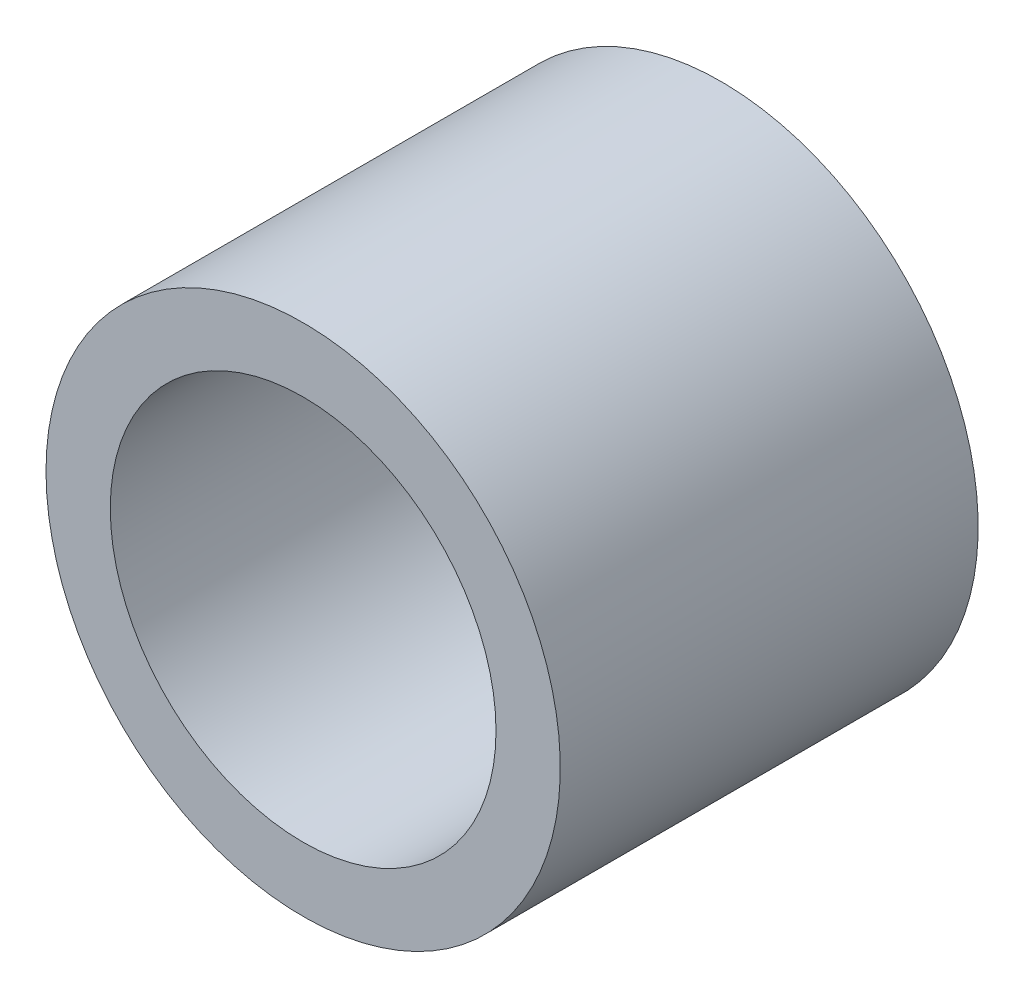
SolidWorks part; units mm, degrees
material "Полиуретан (11671)"
ref_plane "Front" through (0, 0, 0) normal (0, 0, 1) x (1, 0, 0)
ref_plane "Top" through (0, 0, 0) normal (0, 1, 0) x (1, 0, 0)
ref_plane "Right" through (0, 0, 0) normal (1, 0, 0) x (0, 0, -1)
sketch "Эскиз1" plane through (0, 0, 0) normal (0, 0, 1) x (1, 0, 0)
  circle A0 centre (0, 0) radius 16
  circle A1 centre (0, 0) radius 12
  dimension "D1" = 32
  dimension "D2" = 24
extrude "Бобышка-Вытянуть1" add sketch "Эскиз1" along normal blind 26
